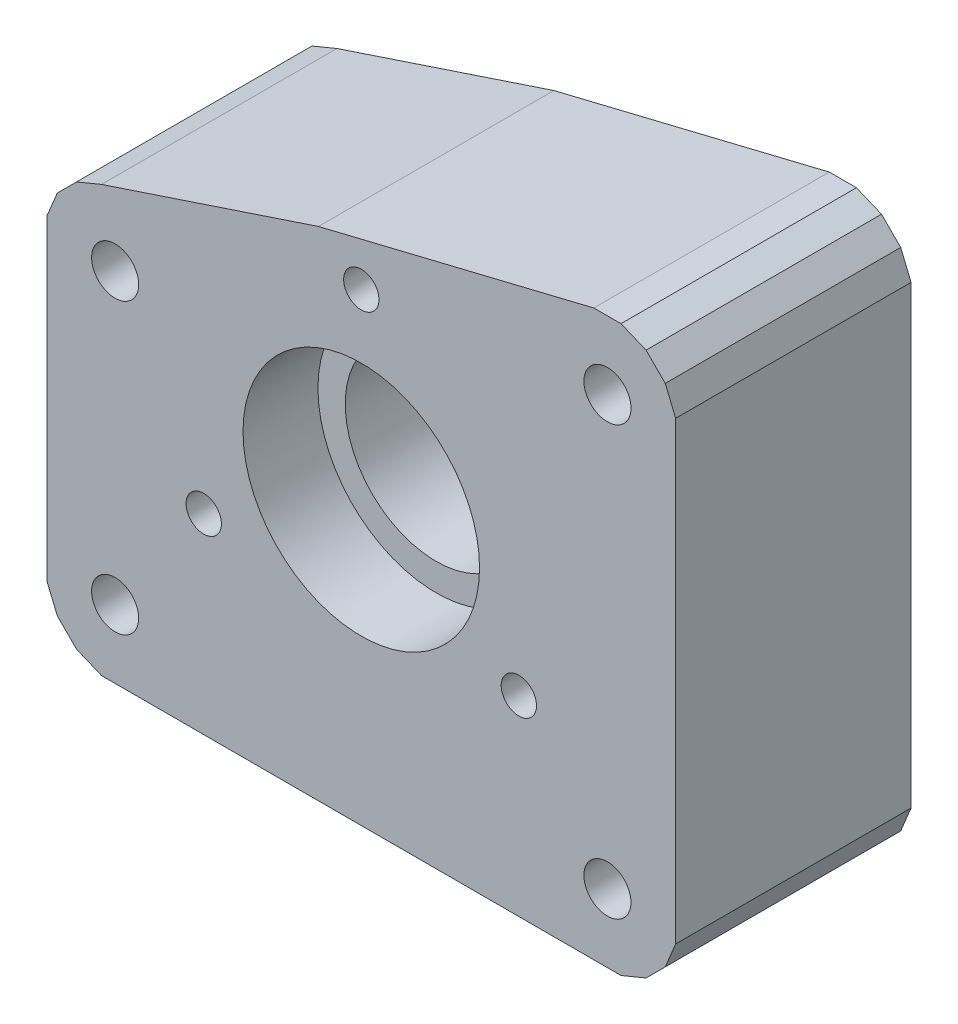
SolidWorks part; units mm, degrees
ref_plane "前视基准面" through (0, 0, 0) normal (0, 0, 1) x (1, 0, 0)
ref_plane "上视基准面" through (0, 0, 0) normal (0, 1, 0) x (1, 0, 0)
ref_plane "右视基准面" through (0, 0, 0) normal (1, 0, 0) x (0, 0, -1)
other "Configuration Table"
sketch "Profile_1" plane through (0, 0, 0) normal (0, 0, 1) x (1, 0, 0)
  line L0 (-24.2681, -26.3751) -> (24.2681, -26.3751)
  line L1 (24.2681, -26.3751) -> (26.6112, -25.4046)
  line L2 (26.6112, -25.4046) -> (28.4046, -23.6112)
  line L3 (28.4046, -23.6112) -> (29.3751, -21.2681)
  line L4 (29.3751, -21.2681) -> (29.3751, 21.2681)
  line L5 (29.3751, 21.2681) -> (28.4046, 23.6112)
  line L6 (28.4046, 23.6112) -> (26.6112, 25.4046)
  line L7 (26.6112, 25.4046) -> (24.2681, 26.3751)
  line L8 (24.2681, 26.3751) -> (21.7319, 26.3751)
  line L9 (21.7319, 26.3751) -> (-3.9994, 20.1061)
  line L10 (-3.9994, 20.1061) -> (-24.2681, 13.3751)
  line L11 (-24.2681, 13.3751) -> (-26.6112, 12.4046)
  line L12 (-26.6112, 12.4046) -> (-28.4046, 10.6112)
  line L13 (-28.4046, 10.6112) -> (-29.3751, 8.2681)
  line L14 (-29.3751, 8.2681) -> (-29.3751, -21.2681)
  line L15 (-29.3751, -21.2681) -> (-28.4046, -23.6112)
  line L16 (-28.4046, -23.6112) -> (-26.6112, -25.4046)
  line L17 (-26.6112, -25.4046) -> (-24.2681, -26.3751)
  circle A0 centre (0, 0) radius 8.5
  circle A1 centre (-23, -20) radius 2.2
  circle A2 centre (23, -20) radius 2.2
  circle A3 centre (-23, 7) radius 2.2
  circle A4 centre (23, 20) radius 2.2
  circle A5 centre (0, 17) radius 1.65
  circle A6 centre (-14.7224, -8.5) radius 1.65
  circle A7 centre (14.7224, -8.5) radius 1.65
extrude "Cartridge_body" add sketch "Profile_1" along normal blind 22 from offset 34
sketch "Profile_2" plane through (0, 0, 0) normal (0, 0, 1) x (1, 0, 0)
  circle A0 centre (0, 0) radius 11.05
extrude "Inboard_608_seat" cut sketch "Profile_2" along normal blind 7.01 from offset 33.99
sketch "Profile_3" plane through (0, 0, 0) normal (0, 0, 1) x (1, 0, 0)
  circle A0 centre (0, 0) radius 11.05
extrude "Outboard_608_seat" cut sketch "Profile_3" along normal blind 7.01 from offset 49
